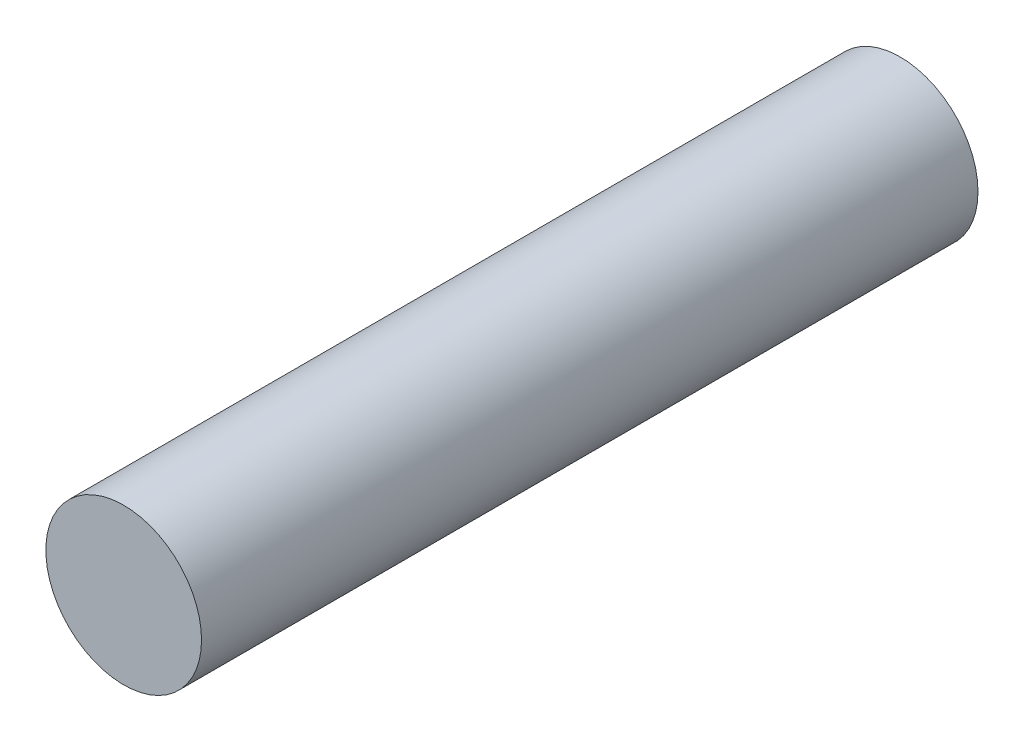
SolidWorks part; units mm, degrees
ref_plane "Front Plane" through (0, 0, 0) normal (0, 0, 1) x (1, 0, 0)
ref_plane "Top Plane" through (0, 0, 0) normal (0, 1, 0) x (1, 0, 0)
ref_plane "Right Plane" through (0, 0, 0) normal (1, 0, 0) x (0, 0, -1)
sketch "Sketch1" plane through (0, 0, 0) normal (0, 0, 1) x (1, 0, 0)
  circle A0 centre (0, 0) radius 3.175
  dimension "D1" = 6.35
extrude "Boss-Extrude1" add sketch "Sketch1" along normal blind 26.59
sketch "Sketch2" plane through (0, 0, 26.59) normal (0, 0, 1) x (1, 0, 0)
  circle A0 centre (0, 0) radius 3.175
  dimension "D1" = 6.35
extrude "Boss-Extrude2" add sketch "Sketch2" along normal blind 5.08
